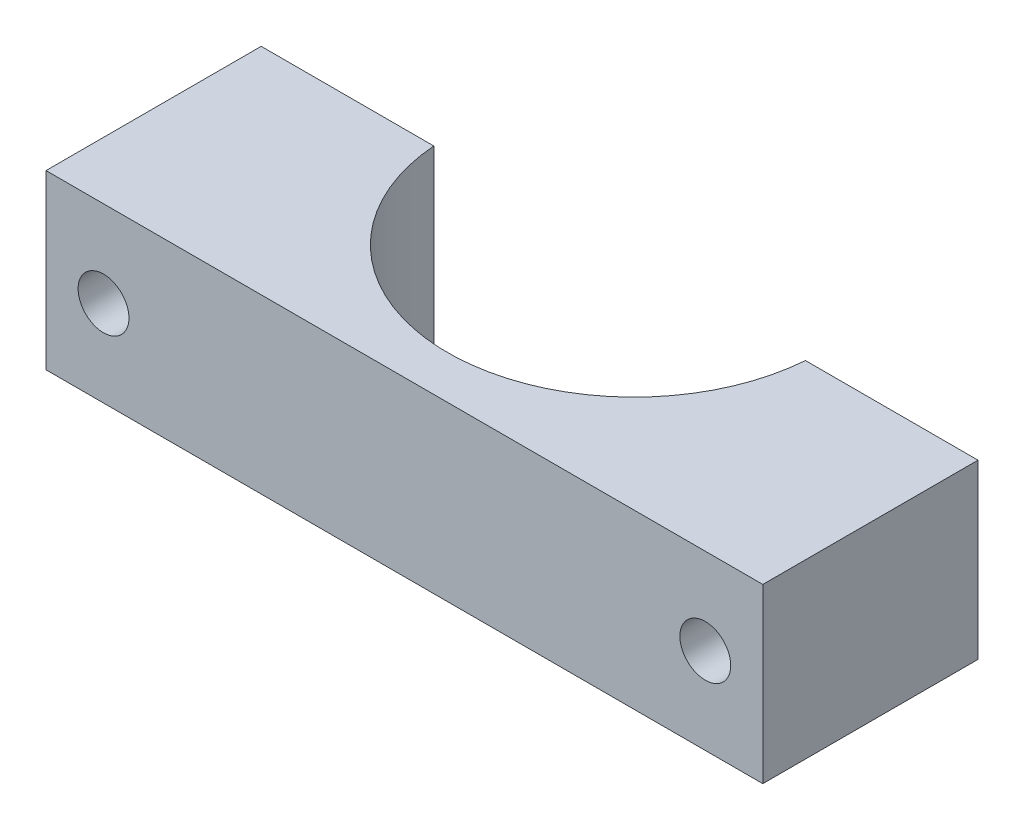
SolidWorks part; units mm, degrees
ref_plane "Front Plane" through (0, 0, 0) normal (0, 0, 1) x (1, 0, 0)
ref_plane "Top Plane" through (0, 0, 0) normal (0, 1, 0) x (1, 0, 0)
ref_plane "Right Plane" through (0, 0, 0) normal (1, 0, 0) x (0, 0, -1)
sketch "Sketch1" plane through (0, 0, 0) normal (0, 1, 0) x (1, 0, 0)
  line L1 (39.563, -1.5826) -> (39.563, -25.3365)
  line L2 (39.563, -25.3365) -> (-39.563, -25.3365)
  line L3 (-39.563, -25.3365) -> (-39.563, -1.5826)
  line L6 (0, 0) -> (-20.513, -1.5826) construction
  line L7 (0, 0) -> (20.513, -1.5826) construction
  line L9 (20.513, -1.5826) -> (39.563, -1.5826)
  line L10 (-20.513, -1.5826) -> (-39.563, -1.5826)
  arc A0 (-20.513, -1.5826) -> (20.513, -1.5826) centre (0, 0) ccw
  point P1 (0, -20.574)
  point P8 (0, -25.3365)
  point P10 (-20.513, -1.5826)
  point P11 (20.513, -1.5826)
  dimension "D1" = 20.574
  dimension "D5" = 171.177
  dimension "D2" = 19.05
  dimension "D3" = 4.7625
extrude "Boss-Extrude1" add sketch "Sketch1" along normal blind 19.05
sketch "Sketch2" plane through (0, 0, 25.3365) normal (0, 0, 1) x (1, 0, 0)
  line L0 (-39.563, 19.05) -> (39.563, 19.05) construction
  line L1 (-39.563, 19.05) -> (-39.563, 0) construction
  line L2 (-39.563, 0) -> (39.563, 0) construction
  line L3 (39.563, 19.05) -> (39.563, 0) construction
  line L4 (-39.563, 19.05) -> (39.563, 19.05) construction
  line L5 (-39.563, 19.05) -> (-39.563, 0) construction
  line L6 (-39.563, 0) -> (39.563, 0) construction
  line L7 (39.563, 19.05) -> (39.563, 0) construction
  line L8 (-39.563, 0) -> (39.563, 19.05) construction
  line L9 (-39.563, 19.05) -> (39.563, 0) construction
  line L10 (-26.863, 19.05) -> (-26.863, 6.35) construction
  line L11 (-26.863, 6.35) -> (-39.563, 6.35) construction
  line L12 (0, 19.05) -> (0, 0) construction
  line L13 (33.213, 9.525) -> (-33.213, 9.525) construction
  circle A1 centre (33.213, 9.525) radius 1.27
  circle A4 centre (-33.213, 9.525) radius 1.27
  point P2 (0, 9.525)
  point P7 (0, 9.525)
  dimension "D2" = 2.54
  dimension "D1" = 12.7
  dimension "D3" = 6.35
extrude "Cut-Extrude1" cut sketch "Sketch2" against normal through all
hole_wizard "#10 Clearance Hole1" positions "Sketch4" profile "Sketch3" hole size "#10" standard "ANSI Inch" end condition through all
sketch "Sketch4" plane through (0, 0, 25.3365) normal (0, 0, 1) x (1, 0, 0)
  point P0 (-33.213, 9.525)
  point P3 (33.213, 9.525)
sketch "Sketch3" plane through (-33.213, 9.525, 25.3365) normal (1, 0, 0) x (0, -1, 0)
  line L0 (0, 0) -> (0, 23.7539)
  line L1 (0, 23.7539) -> (2.8067, 23.7539)
  line L2 (2.8067, 23.7539) -> (2.8067, 0)
  line L5 (2.8067, 0) -> (0, 0)
  line L11 (0, -6.35) -> (0, 107.95) construction
  dimension "Thru Hole Dia." = 5.6134
  dimension "Thru Hole Depth" = 23.7539
